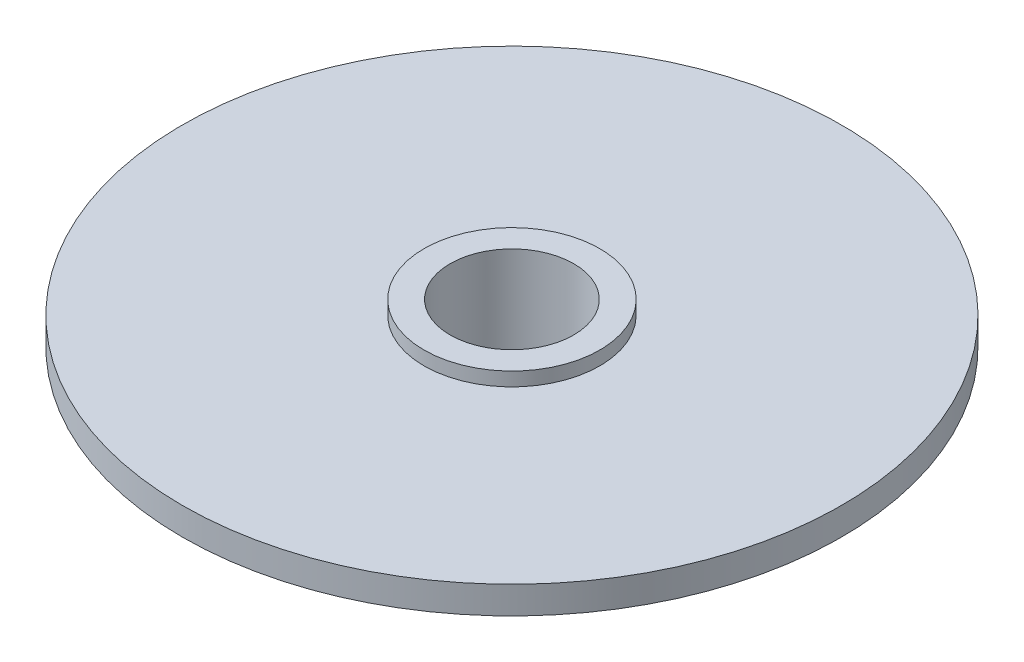
SolidWorks part; units mm, degrees
ref_plane "前视基准面" through (0, 0, 0) normal (0, 0, 1) x (1, 0, 0)
ref_plane "上视基准面" through (0, 0, 0) normal (0, 1, 0) x (1, 0, 0)
ref_plane "右视基准面" through (0, 0, 0) normal (1, 0, 0) x (0, 0, -1)
sketch "草图1" plane through (0, 0, 0) normal (0, 1, 0) x (1, 0, 0)
  circle A0 centre (0, 0) radius 120
  circle A1 centre (0, 0) radius 22.5
extrude "凸台-拉伸1" add sketch "草图1" along normal blind 10
sketch "草图2" plane through (0, 0, 0) normal (0, -1, 0) x (1, 0, 0)
  circle A0 centre (0, 0) radius 22.5
  circle A1 centre (0, 0) radius 32
extrude "凸台-拉伸2" add sketch "草图2" along normal blind 40
sketch "草图3" plane through (0, 10, 0) normal (0, 1, 0) x (1, 0, 0)
  circle A0 centre (0, 0) radius 22.5
  circle A1 centre (0, 0) radius 32
extrude "凸台-拉伸3" add sketch "草图3" along normal blind 5
